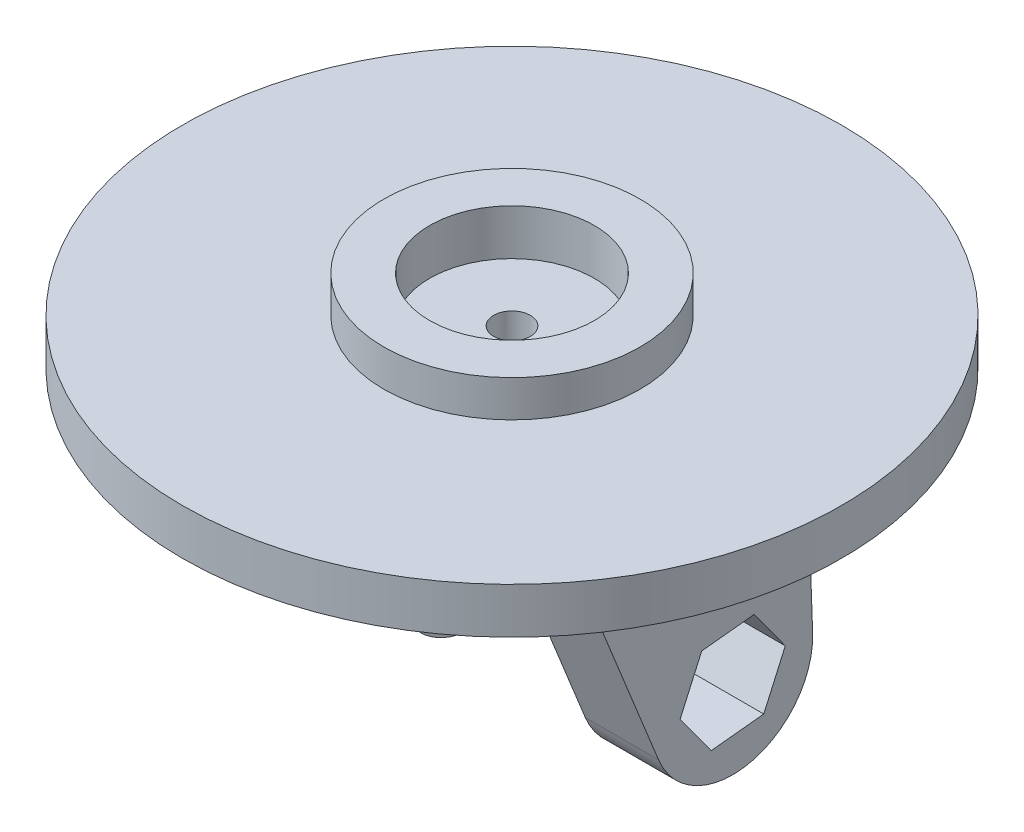
SolidWorks part; units mm, degrees
ref_plane "前视基准面" through (0, 0, 0) normal (0, 0, 1) x (1, 0, 0)
ref_plane "上视基准面" through (0, 0, 0) normal (0, 1, 0) x (1, 0, 0)
ref_plane "右视基准面" through (0, 0, 0) normal (1, 0, 0) x (0, 0, -1)
other "Configuration Table"
sketch "草图1" plane through (0, 0, 0) normal (0, 1, 0) x (1, 0, 0)
  circle A0 centre (0, 0) radius 7
extrude "凸台-拉伸1" add sketch "草图1" along normal blind 4
sketch "草图2" plane through (0, 4, 0) normal (0, 1, 0) x (1, 0, 0)
  circle A0 centre (0, 0) radius 4.5
  circle A1 centre (0, 0) radius 7
  dimension "D1" = 2.5
extrude "凸台-拉伸2" add sketch "草图2" along normal blind 2.5
sketch "草图3" plane through (0, 4, 0) normal (0, 1, 0) x (1, 0, 0)
  circle A0 centre (0, 0) radius 1
extrude "切除-拉伸1" cut sketch "草图3" against normal blind 2.5
sketch "草图4" plane through (0, 0, 0) normal (0, -1, 0) x (1, 0, 0)
  line L1 (1.4591, -2.4909) -> (2.8867, 0.0182)
  line L2 (2.8867, 0.0182) -> (1.4276, 2.509)
  line L3 (1.4276, 2.509) -> (-1.4591, 2.4909)
  line L4 (-1.4591, 2.4909) -> (-2.8867, -0.0182)
  line L5 (-2.8867, -0.0182) -> (-1.4276, -2.509)
  line L6 (-1.4276, -2.509) -> (1.4591, -2.4909)
  circle A0 centre (0, 0) radius 2.5 construction
  dimension "D1" = 2.5
extrude "切除-拉伸2" cut sketch "草图4" against normal blind 2
ref_plane "基准面2" through (0, 2, 0) normal (0, 1, 0) x (1, 0, 0)
sketch "草图5" plane through (0, 2, 0) normal (0, 1, 0) x (1, 0, 0)
  circle A0 centre (0, 0) radius 18
  circle A1 centre (0, 0) radius 7
extrude "凸台-拉伸3" add sketch "草图5" along normal blind 2.5
ref_plane "基准面3" through (7, 0, 0) normal (1, 0, 0) x (0, 0, -1)
sketch "草图6" plane through (7, 0, 0) normal (1, 0, 0) x (0, 0, -1)
  line L0 (-6.4592, 2) -> (-0.9946, -11.5322)
  line L1 (19.8, 2) -> (-19.8, 2) construction
  line L3 (7.4209, -9.7401) -> (7, 2)
  line L4 (7, 0) -> (7, 2) construction
  line L5 (7, 2) -> (-6.4592, 2)
  line L7 (4.233, -7.2609) -> (1.3617, -7.5591)
  line L8 (1.3617, -7.5591) -> (0.1843, -10.1949)
  line L9 (0.1843, -10.1949) -> (1.8783, -12.5324)
  line L10 (1.8783, -12.5324) -> (4.7496, -12.2341)
  line L11 (4.7496, -12.2341) -> (5.9269, -9.5983)
  line L12 (5.9269, -9.5983) -> (4.233, -7.2609)
  arc A0 (-0.9946, -11.5322) -> (7.4209, -9.7401) centre (3.0556, -9.8966) ccw
  circle A1 centre (3.0556, -9.8966) radius 2.5 construction
  point P9 (0, 0)
  dimension "D1" = 2.5
extrude "凸台-拉伸4" add sketch "草图6" along normal mid plane 4
mirror "镜向1" about plane through (0, 0, 0) normal (1, 0, 0) of "凸台-拉伸4"
